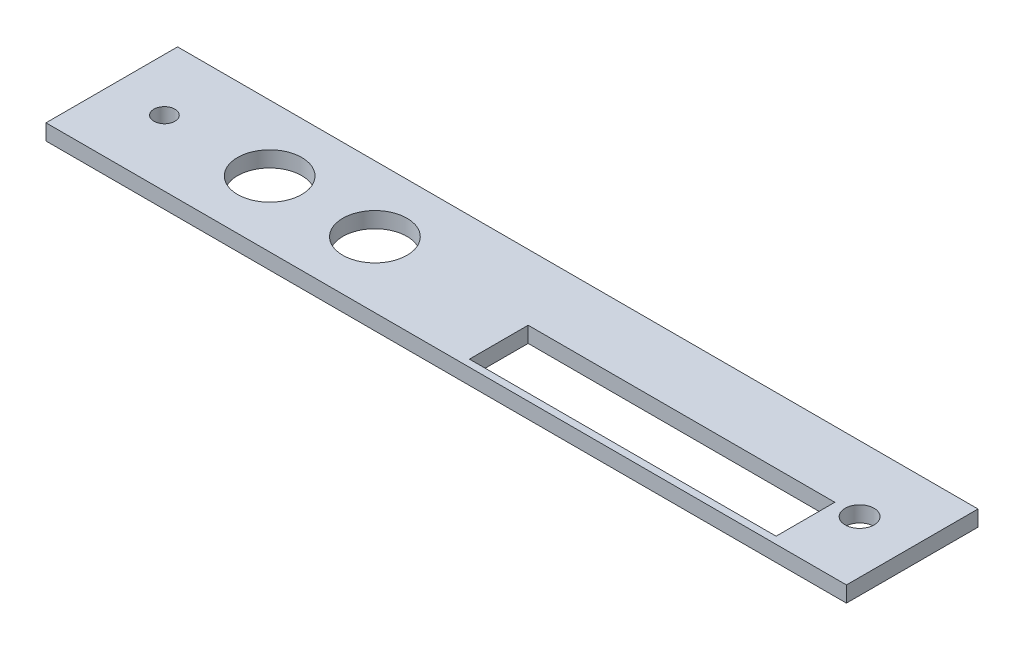
SolidWorks part; units mm, degrees
material "Custom Plastic"
ref_plane "Plan de face" through (0, 0, 0) normal (0, 0, 1) x (1, 0, 0)
ref_plane "Plan de dessus" through (0, 0, 0) normal (0, 1, 0) x (1, 0, 0)
ref_plane "Plan de droite" through (0, 0, 0) normal (1, 0, 0) x (0, 0, -1)
sketch "Esquisse1" plane through (0, 0, 0) normal (0, 1, 0) x (1, 0, 0)
  line L3 (-76.5453, -14.573) -> (75.5547, -14.573) construction
  line L6 (-86.2453, 10.427) -> (78.7547, 10.427) construction
  line L12 (-76.5453, -14.573) -> (75.5547, -14.573)
  line L13 (65.5547, -2.073) -> (75.5547, -2.073) construction
  line L15 (-86.2453, -14.573) -> (78.7547, -14.573) construction
  line L20 (-66.5453, -2.073) -> (-76.5453, -2.073) construction
  line L26 (65.5547, -45.0903) -> (65.5547, -50045.0903) construction
  line L28 (-66.5453, 45.927) -> (-66.5453, 0.927) construction
  line L36 (-76.5453, 10.427) -> (75.5547, 10.427)
  line L37 (75.5547, 10.427) -> (75.5547, -14.573)
  line L44 (-76.5453, 10.427) -> (-76.5453, -14.573)
  circle A12 centre (65.5547, -2.073) radius 2.75
  circle A15 centre (-66.5453, -2.073) radius 2
  dimension "D3" = 4
  dimension "D5" = 5.5
  dimension "D1" = 10
  dimension "D2" = 152.1
extrude "Boss.-Extru.1" add sketch "Esquisse1" along normal blind 3
sketch "Esquisse3" plane through (0, 0, 0) normal (0, 1, 0) x (1, 0, 0)
  line L33 (75.5547, -14.573) -> (75.5547, -24.573) construction
  line L40 (-76.5453, -2.073) -> (-26.5453, -2.073) construction
  line L41 (-76.5453, 10.427) -> (-76.5453, -14.573) construction
  line L43 (2.5743, -13.2329) -> (60.8474, -13.2329)
  line L44 (2.5743, -13.2329) -> (2.5743, -2.073)
  line L45 (2.5743, -2.073) -> (60.8474, -2.073)
  line L46 (60.8474, -13.2329) -> (60.8474, -2.073)
  circle A5 centre (-46.5453, -2.073) radius 6.1
  circle A6 centre (-26.5453, -2.073) radius 6.1
  point P10 (9.0819, -7.573)
  point P15 (30.4566, -3.573)
  point P16 (9.0819, -12.073)
  point P17 (30.4566, -12.073)
  dimension "D13" = 12.2
  dimension "D7" = 10
  dimension "D14" = 20
  dimension "D15" = 30
extrude "Enlèv. mat.-Extru.2" cut sketch "Esquisse3" along normal through all
